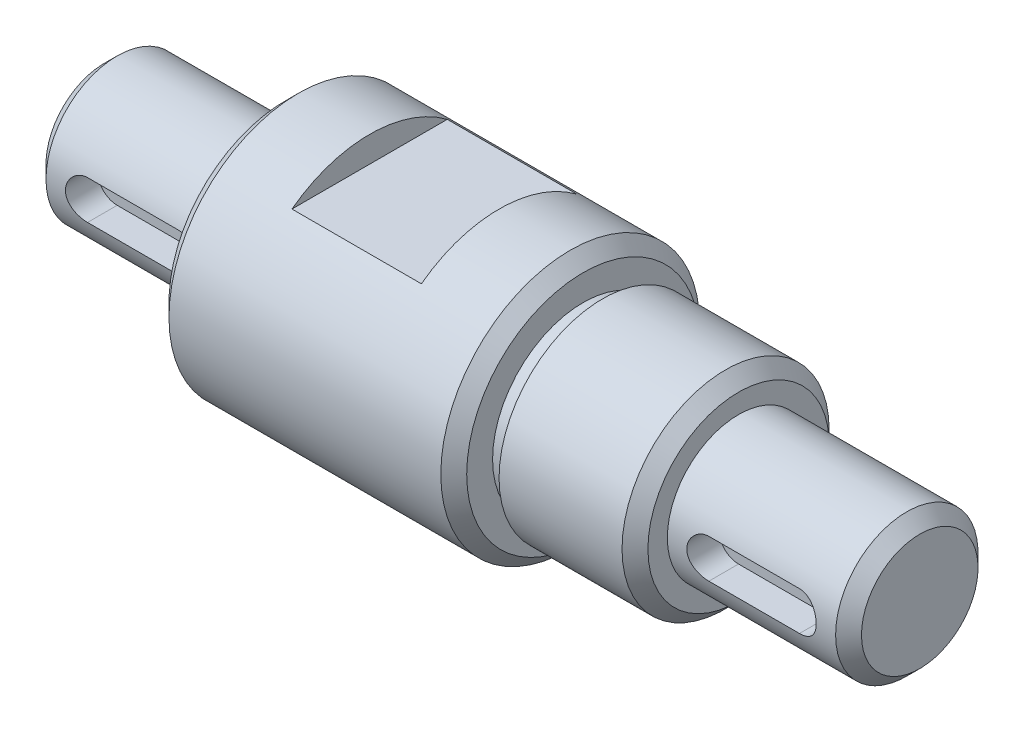
SolidWorks part; units mm, degrees
material "Plain Carbon Steel"
ref_plane "Front Plane" through (0, 0, 0) normal (0, 0, 1) x (1, 0, 0)
ref_plane "Top Plane" through (0, 0, 0) normal (0, 1, 0) x (1, 0, 0)
ref_plane "Right Plane" through (0, 0, 0) normal (1, 0, 0) x (0, 0, -1)
sketch "Sketch1" plane through (0, 0, 0) normal (0, 0, 1) x (1, 0, 0)
  line L0 (0, 0) -> (126, 0) construction
  line L1 (0, 0) -> (0, 11)
  line L2 (0, 11) -> (28, 11)
  line L3 (28, 11) -> (28, 20)
  line L4 (28, 20) -> (74, 20)
  line L5 (74, 20) -> (74, 14)
  line L6 (74, 14) -> (77, 14)
  line L7 (77, 14) -> (77, 16)
  line L8 (77, 16) -> (98, 16)
  line L9 (98, 16) -> (98, 11)
  line L10 (98, 11) -> (126, 11)
  line L11 (126, 11) -> (126, 0)
  line L12 (126, 0) -> (0, 0)
  dimension "D1" = 28
  dimension "D2" = 46
  dimension "D3" = 21
  dimension "D4" = 28
  dimension "D5" = 126
  dimension "D6" = 11
  dimension "D7" = 20
  dimension "D8" = 14
  dimension "D9" = 16
revolve "Revolve1" add sketch "Sketch1" angle 360 about L0
chamfer "Chamfer1" distance 2 angle 45 5 edges at (126, 0, 11) (98, 0, 16) (74, 0, 20) (28, 0, 20) (0, 0, 11)
sketch "Sketch2" plane through (0, 0, 0) normal (0, 0, 1) x (1, 0, 0)
  line L0 (41, 16) -> (61, 16)
  line L1 (61, 16) -> (61, 22)
  line L2 (61, 22) -> (41, 22)
  line L3 (41, 22) -> (41, 16)
  dimension "D1" = 41
  dimension "D2" = 20
  dimension "D3" = 16
  dimension "D4" = 6
extrude "Cut-Extrude1" cut sketch "Sketch2" against normal through all and the other way through all
ref_plane "Plane1" through (0, 0, 11) normal (0, 0, 1) x (1, 0, 0)
sketch "Sketch3" plane through (0, 0, 11) normal (0, 0, 1) x (1, 0, 0)
  line L0 (8, 3) -> (22, 3)
  line L1 (22, -3) -> (8, -3)
  line L2 (8, 0) -> (22, 0) construction
  line L3 (104, 3) -> (118, 3)
  line L4 (118, -3) -> (104, -3)
  line L5 (104, 0) -> (118, 0) construction
  arc A0 (22, -3) -> (22, 3) centre (22, 0) ccw
  arc A1 (8, 3) -> (8, -3) centre (8, 0) ccw
  arc A2 (118, -3) -> (118, 3) centre (118, 0) ccw
  arc A3 (104, 3) -> (104, -3) centre (104, 0) ccw
  point P6 (5, 0)
  point P7 (25, 0)
  point P15 (101, 0)
  point P16 (121, 0)
  dimension "D1" = 6
  dimension "D2" = 20
  dimension "D3" = 5
  dimension "D4" = 6
  dimension "D5" = 20
  dimension "D6" = 121
extrude "Cut-Extrude2" cut sketch "Sketch3" against normal blind 5
